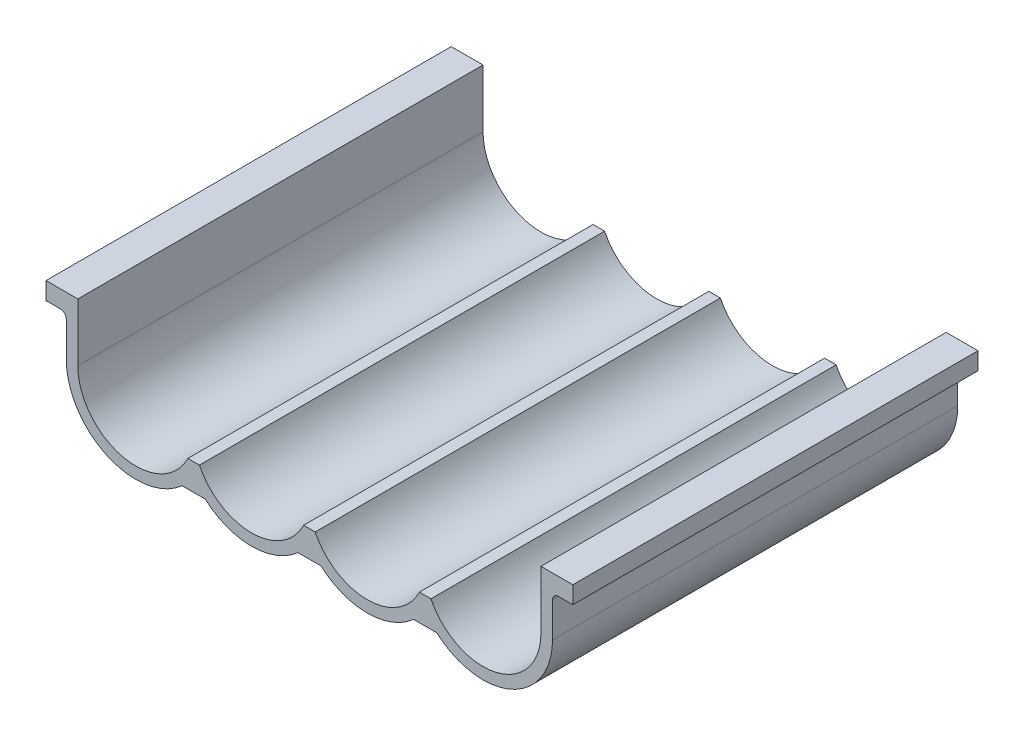
SolidWorks part; units mm, degrees
ref_plane "Front" through (0, 0, 0) normal (0, 0, 1) x (1, 0, 0)
ref_plane "Top" through (0, 0, 0) normal (0, 1, 0) x (1, 0, 0)
ref_plane "Right" through (0, 0, 0) normal (1, 0, 0) x (0, 0, -1)
sketch "Sketch1" plane through (0, 0, 0) normal (0, 0, 1) x (1, 0, 0)
  line L0 (0, 0) -> (5.5, 0)
  line L1 (24.5, -14.3589) -> (26.5, -14.3589)
  line L2 (44.5, -14.3589) -> (46.5, -14.3589)
  line L3 (0, 0) -> (0, -3)
  line L5 (45.5, -7.7789) -> (45.5, -22.3818) construction
  line L7 (91, 0) -> (91, -3)
  line L8 (66.5, -14.3589) -> (64.5, -14.3589)
  line L9 (91, 0) -> (85.5, 0)
  line L11 (5.5, -10) -> (5.5, 0)
  line L12 (85.5, -10) -> (85.5, 0)
  line L19 (23.5, -18.9443) -> (27.5, -18.9443)
  line L20 (43.5, -18.9443) -> (47.5, -18.9443)
  line L21 (67.5, -18.9443) -> (63.5, -18.9443)
  line L22 (3.5, -10) -> (3.5, -3)
  line L23 (0, -3) -> (3.5, -3)
  line L24 (91, -3) -> (87.5, -3)
  line L25 (87.5, -10) -> (87.5, -3)
  arc A1 (26.5, -14.3589) -> (44.5, -14.3589) centre (35.5, -10) ccw
  arc A2 (3.5, -10) -> (23.5, -18.9443) centre (15.5, -10) ccw
  arc A3 (64.5, -14.3589) -> (46.5, -14.3589) centre (55.5, -10) cw
  arc A6 (24.5, -14.3589) -> (5.5, -10) centre (15.5, -10) cw
  arc A7 (66.5, -14.3589) -> (85.5, -10) centre (75.5, -10) ccw
  arc A8 (63.5, -18.9443) -> (47.5, -18.9443) centre (55.5, -10) cw
  arc A9 (27.5, -18.9443) -> (43.5, -18.9443) centre (35.5, -10) ccw
  arc A10 (87.5, -10) -> (67.5, -18.9443) centre (75.5, -10) cw
  point P5 (45.5, -14.3589)
  point P20 (87.5, -10.0839)
  point P38 (87.5, -7)
  point P48 (45.5, -18.9443)
  dimension "D2" = 10
  dimension "D8" = 20
  dimension "D4" = 10
  dimension "D10" = 2
  dimension "D9" = 12
  dimension "D16" = 12
  dimension "D17" = 4
  dimension "D3" = 10
  dimension "D5" = 10
  dimension "D7" = 5.5
  dimension "D11" = 4
  dimension "D12" = 10
  dimension "D13" = 2
  dimension "D14" = 3
extrude "Boss-Extrude1" add sketch "Sketch1" along normal blind 70
ref_plane "Plane1" through (45.5, 0, 0) normal (-1, 0, 0) x (0, 0, 1)
sketch "Sketch7" plane through (0, -14.3589, 0) normal (0, 1, 0) x (1, 0, 0)
  line L0 (45.5, -70) -> (45.5, 0) construction
  line L1 (46.5, -70) -> (44.5, -70) construction
  line L2 (46.5, 0) -> (44.5, 0) construction
  point P6 (45.5, -55)
  point P8 (45.5, -15)
  dimension "D1" = 15
  dimension "D2" = 15
sketch "Sketch8" plane through (0, 0, 0) normal (0, 1, 0) x (1, 0, 0)
  line L0 (87.75, 0) -> (87.75, -70) construction
  line L1 (91, 0) -> (85.5, 0) construction
  line L2 (91, -70) -> (85.5, -70) construction
  line L4 (85.5, -70) -> (85.5, 0) construction
  point P8 (87.75, -55)
  point P9 (87.75, -15)
  dimension "D1" = 2.25
  dimension "D2" = 15
  dimension "D3" = 15
fillet "Fillet2" radius 1 2 edges at (87.5, -3, 35) (3.5, -3, 35)
